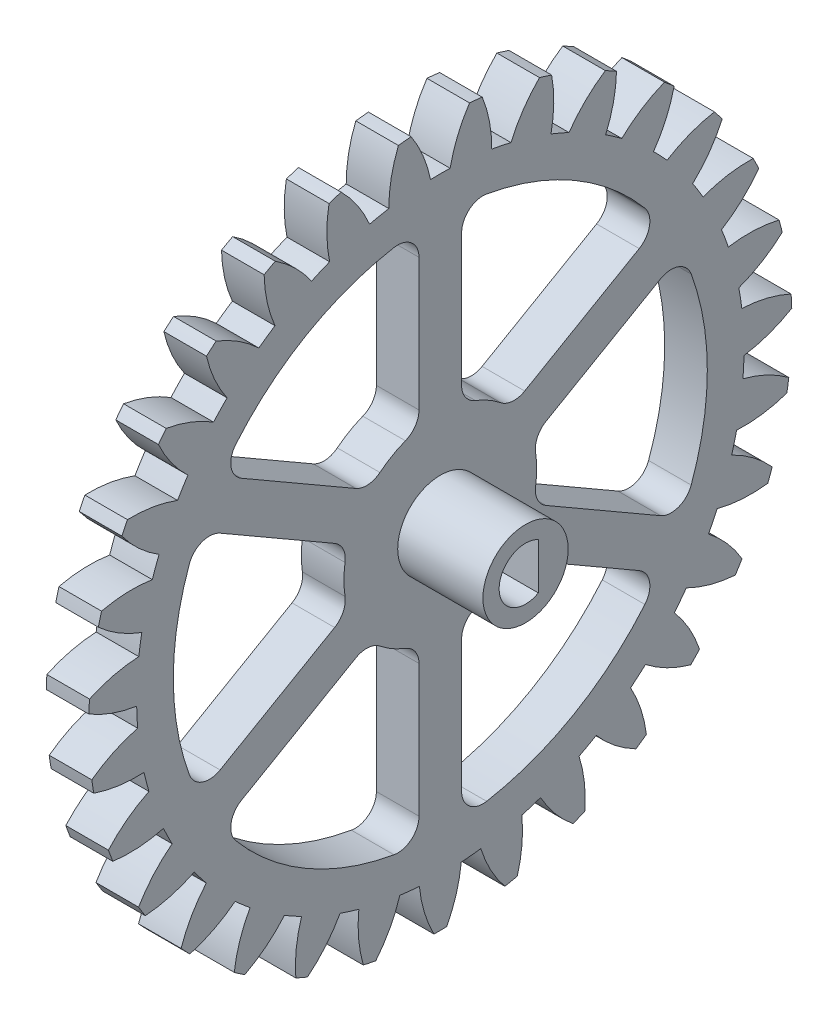
SolidWorks part; units mm, degrees
ref_plane "Plane1" through (0, 0, 0) normal (0, 0, 1) x (1, 0, 0)
ref_plane "Plane2" through (0, 0, 0) normal (0, 1, 0) x (1, 0, 0)
ref_plane "Plane3" through (0, 0, 0) normal (1, 0, 0) x (0, 0, -1)
sketch "HoldingSke" plane through (0, 0, 0) normal (0, 1, 0) x (1, 0, 0)
  line L0 (0, 0) -> (174.1764, -104.6557)
  line L1 (-15, 0) -> (100, 0) construction
  line L2 (0, 0) -> (-2.1039, 2.3779)
  line L3 (0, 0) -> (-11.863, 4.5341)
  line L4 (0, 0) -> (7.4025, 4.4479)
  line L5 (0, 0) -> (-47.5972, -17.7524)
  line L6 (0, 0) -> (-5.2639, -3.5516)
  line L7 (-2.1039, 2.3779) -> (8.8308, 51.9871)
  line L8 (-76.2, 54.61) -> (-72.771, 54.61)
  line L9 (-71.009, 38.7566) -> (-53.1078, 45.2721)
  line L10 (-76.2, 71.12) -> (104.1128, 71.12)
  line L11 (0, 0) -> (-6.35, 0)
  line L12 (-76.2, 101.6) -> (-76.0857, 101.6)
  line L13 (24.9733, 27.94) -> (52.9518, 28.4284)
  line L14 (24.9733, 27.94) -> (24.9746, 27.94)
  line L15 (24.9733, 27.94) -> (100.4006, 29.5858)
  circle A0 centre (0, 0) radius 1.5875
  circle A1 centre (0, 0) radius 38.1
  circle A2 centre (0, 0) radius 38.1
  circle A3 centre (0, 0) radius 1.5875
  dimension "MHD" = 76.2
  dimension "Hub_dia" = 76.2
  dimension "Bore" = 3.175
  dimension "MBD" = 3.175
  dimension "Num_teeth" = 31
  dimension "Pitch" = 203.2
  dimension "Overall_len" = 50.8
  dimension "Show_teeth" = 31
  dimension "Thickness" = 6.35
  dimension "OAL" = 50.8001
  dimension "T_dim" = 3.429
  dimension "Ap" = 20
  dimension "H" = 19.05
  dimension "Pitch_radius" = 180.3128
  dimension "Width" = 6.35
  dimension "Backlash" = 0.1143
  dimension "Addendum_fac" = 1
  dimension "Dedendum_fac" = 1.25
  dimension "Clearance_fac" = 0.25
  dimension "Dedendum_add" = 0.0013
sketch "BasProSke" plane through (0, 0, 0) normal (0, 1, 0) x (1, 0, 0)
  line L0 (-10, 0) -> (60, 0) construction
  line L1 (0, 0) -> (0, 52.3875)
  line L2 (0, 0) -> (6.35, 0)
  line L3 (6.35, 0) -> (6.35, 52.3875)
  line L4 (6.35, 52.3875) -> (0, 52.3875)
  dimension "Thickness" = 6.35
  dimension "Diameter" = 104.775
revolve "Base-Revolve" add sketch "BasProSke" angle 360 about L0
sketch "TooCutSke" plane through (0, 0, 0) normal (1, 0, 0) x (0, 0, -1)
  line L1 (0, 0) -> (0, 107) construction
  line L2 (0, 0) -> (-2.6926, 49.1388) construction
  line L3 (0, 0) -> (-9.9467, 97.8137) construction
  line L4 (-2.6926, 49.1388) -> (-4.9733, 48.9069) construction
  arc A0 (1.4638, 45.2188) -> (-1.4638, 45.2188) centre (0, 0) ccw
  arc A1 (4.3725, 52.2302) -> (-4.3725, 52.2302) centre (0, 0) ccw
  circle A2 centre (0, 0) radius 49.2125 construction
  circle A3 centre (0, 0) radius 46.2446 construction
  arc A4 (-1.4638, 45.2188) -> (-4.3725, 52.2302) centre (-20.7595, 41.3232) ccw
  arc A5 (4.3725, 52.2302) -> (1.4638, 45.2188) centre (20.7595, 41.3232) ccw
  dimension "Root_dia" = 90.485
  dimension "Overcut_dia" = 104.8258
  dimension "Pitch_dia" = 98.425
  dimension "Base_dia" = 92.4892
  dimension "Flank_rad" = 19.685
  dimension "Half_ang" = 5.806
  dimension "Half_CT" = 2.2925
extrude "ToothCut" cut sketch "TooCutSke" along normal through all
fillet "Breaks" [suppressed] radius 0.0635
fillet "RootFillets" [suppressed] radius 0.795
pattern_circular "TeethCuts" count 31 every 11.613 about axis through (-10, 0, 0) along (1, 0, 0) of "ToothCut", "RootFillets", "Breaks"
sketch "HubNeaOneSke" plane through (0, 0, 0) normal (-1, 0, 0) x (0, 0, 1)
  circle A0 centre (0, 0) radius 38.1
  dimension "Diameter" = 76.2
extrude "HubNearOne" [suppressed] add sketch "HubNeaOneSke" along normal blind 44.4501
sketch "HubNeaBotSke" plane through (0, 0, 0) normal (-1, 0, 0) x (0, 0, 1)
  circle A0 centre (0, 0) radius 38.1
  dimension "Diameter" = 76.2
extrude "HubNearBoth" [suppressed] add sketch "HubNeaBotSke" along normal blind 22.225
ref_plane "FarPln" through (6.35, 0, 0) normal (1, 0, 0) x (0, 0, -1)
sketch "HubFarSke" plane through (6.35, 0, 0) normal (1, 0, 0) x (0, 0, -1)
  circle A0 centre (0, 0) radius 38.1
  dimension "Diameter" = 76.2
extrude "HubFar" [suppressed] add sketch "HubFarSke" along normal blind 22.225
sketch "BorSke" plane through (0, 0, 0) normal (1, 0, 0) x (0, 0, -1)
  circle A0 centre (0, 0) radius 1.5875
  dimension "Diameter" = 3.175
extrude "Bore" cut sketch "BorSke" along normal mid plane 101.6001
sketch "KeySke" plane through (0, 0, 0) normal (1, 0, 0) x (0, 0, -1)
  line L0 (-0.127, 0) -> (-0.127, 1.8415)
  line L1 (-0.127, 1.8415) -> (0.127, 1.8415)
  line L2 (0.127, 1.8415) -> (0.127, 0)
  line L3 (0, 0) -> (0, 34) construction
  line L4 (-0.127, 0) -> (0.127, 0)
  dimension "Offset" = 1.8415
  dimension "Width" = 0.254
extrude "Keyway" [suppressed] cut sketch "KeySke" along normal mid plane 101.6001
pattern_circular "Keyway2" [suppressed] count 2 every 90 about axis through (-10, 0, 0) along (1, 0, 0)
sketch "Sketch1" plane through (6.35, 0, 0) normal (1, 0, 0) x (0, 0, -1)
  circle A0 centre (0, 0) radius 6.35
  dimension "D1" = 12.7
extrude "Boss-Extrude1" add sketch "Sketch1" along normal blind 12.7
sketch "Sketch2" plane through (19.05, 0, 0) normal (1, 0, 0) x (0, 0, -1)
  line L0 (1.905, 3.4454) -> (1.905, -3.4454)
  line L1 (3.937, 0) -> (-3.937, 0)
  circle A0 centre (0, 0) radius 3.937
  dimension "D1" = 7.874
  dimension "D2" = 5.842
extrude "Cut-Extrude1" cut sketch "Sketch2" against normal through all contours L0 A0 L1 | L1 A0 L0
sketch "Sketch3" plane through (6.35, 0, 0) normal (1, 0, 0) x (0, 0, -1)
  line L0 (0, 39.781) -> (0, -39.781) construction
  line L1 (-34.4514, 19.8905) -> (34.4514, -19.8905) construction
  line L2 (-34.4514, -19.8905) -> (34.4514, 19.8905) construction
  line L3 (-36.0389, 17.1409) -> (32.8639, -22.6401)
  line L4 (-32.8639, 22.6401) -> (36.0389, -17.1409)
  line L5 (-3.175, 39.781) -> (-3.175, -39.781)
  line L6 (3.175, 39.781) -> (3.175, -39.781)
  line L7 (-32.8639, -22.6401) -> (36.0389, 17.1409)
  line L8 (-36.0389, -17.1409) -> (32.8639, 22.6401)
  circle A0 centre (0, 0) radius 39.781
  circle A1 centre (0, 0) radius 14.3671
  dimension "D9" = 79.562
  dimension "D10" = 28.7342
  dimension "D1" = 60
  dimension "D2" = 60
  dimension "D3" = 3.175
  dimension "D4" = 3.175
  dimension "D5" = 3.175
  dimension "D6" = 3.175
  dimension "D7" = 3.175
  dimension "D8" = 3.175
extrude "Cut-Extrude2" cut sketch "Sketch3" against normal through all contours A1 L5 A0 L4 | A1 L3 A0 L8 | A1 L7 A0 L5 | A1 L6 A0 L3 | A1 L4 A0 L7 | A1 L8 A0 L6
fillet "Fillet1" radius 3.175 24 edges at (3.175, 4.2563, 13.7222) (3.175, -9.7556, -10.5472) (3.175, -14.0119, 3.175) (3.175, 14.0119, 3.175) (3.175, -4.2563, 13.7222) (3.175, 9.7556, -10.5472) (3.175, -22.5767, 32.754) (3.175, 17.0774, -35.929) (3.175, -9.7556, 10.5472) (3.175, 4.2563, -13.7222) (3.175, -14.0119, -3.175) (3.175, 14.0119, -3.175) (3.175, 17.0774, 35.929) (3.175, -22.5767, -32.754) (3.175, -39.6541, -3.175) (3.175, 39.6541, -3.175) (3.175, -4.2563, -13.7222) (3.175, 9.7556, 10.5472) (3.175, -17.0774, 35.929) (3.175, 22.5767, -32.754) (3.175, -17.0774, -35.929) (3.175, 22.5767, 32.754) (3.175, -39.6541, 3.175) (3.175, 39.6541, 3.175)
equation "' \"Pitch@HoldingSke\" = 4"
equation "' \"Num_teeth@HoldingSke\" = 12"
equation "' \"Ap@HoldingSke\" =  20"
equation "' \"Ap@HoldingSke\" = 20"
equation "' \"Width@HoldingSke\" = 0.5"
equation "' \"Hub_dia@HoldingSke\"= 1"
equation "' \"Hub_dia@HoldingSke\" = 1"
equation "' \"Overall_len@HoldingSke\" = 1.0"
equation "' \"Bore@HoldingSke\" = 0.75"
equation "' \"T_dim@HoldingSke\" = 0.85"
equation "' \"Width@KeySke\" = 0.25"
equation "' \"Show_teeth@HoldingSke\" = 13"
equation "' \"Backlash@HoldingSke\" = 0.009"
equation "' \"Addendum_fac@HoldingSke\" = 1.0"
equation "' \"Dedendum_fac@HoldingSke\" = 1.25"
equation "' \"Dedendum_add@HoldingSke\" = 0.00005"
equation "' \"Clearance_fac@HoldingSke\" = 0.25"
equation "' \"Pitch@HoldingSke\" = 0.5"
equation "' \"Num_teeth@HoldingSke\" = 23"
equation "' \"Show_teeth@HoldingSke\" = 23"
equation "' \"Backlash@HoldingSke\" = 0.0375"
equation "\"Overcut_dia@TooCutSke\" = (\"Num_teeth@HoldingSke\" + 2 * \"Addendum_fac@HoldingSke\") / \"Pitch@HoldingSke\" + 0.002"
equation "\"Pitch_dia@TooCutSke\" = \"Num_teeth@HoldingSke\" / \"Pitch@HoldingSke\""
equation "\"Base_dia@TooCutSke\" = \"Num_teeth@HoldingSke\" / \"Pitch@HoldingSke\" * cos((\"Ap@HoldingSke\"  * 3.14159265 / 180))"
equation "\"Root_dia@TooCutSke\" = (\"Num_teeth@HoldingSke\" + 2) / \"Pitch@HoldingSke\" - 2 * (\"Addendum_fac@HoldingSke\" + \"Dedendum_fac@HoldingSke\") / \"Pitch@HoldingSke\" - \"Dedendum_add@HoldingSke\" * 2"
equation "\"Half_ang@TooCutSke\" = 180 / \"Num_teeth@HoldingSke\""
equation "\"Half_CT@TooCutSke\" = \"Num_teeth@HoldingSke\" / \"Pitch@HoldingSke\" * sin((3.14159265 / 2 / \"Num_teeth@HoldingSke\")) / 2 - 7 * \"Backlash@HoldingSke\" / 4"
equation "\"Flank_rad@TooCutSke\" = \"Num_teeth@HoldingSke\" / \"Pitch@HoldingSke\" / 5"
equation "\"Radius@RootFillets\" = \"Clearance_fac@HoldingSke\" / \"Pitch@HoldingSke\" + \"Dedendum_add@HoldingSke\""
equation "\"Break_rad@Breaks\" = 0.02 / \"Pitch@HoldingSke\""
equation "\"Thickness@HoldingSke\" = \"Width@HoldingSke\""
equation "\"OAL@HoldingSke\" = \"Thickness@HoldingSke\""
equation "\"MHD@HoldingSke\" = (\"Num_teeth@HoldingSke\" + 2) / \"Pitch@HoldingSke\" - 2 * (\"Addendum_fac@HoldingSke\" + \"Dedendum_fac@HoldingSke\")  / \"Pitch@HoldingSke\" - \"Dedendum_add@HoldingSke\" * 2"
equation "\"MBD@HoldingSke\" = (\"Num_teeth@HoldingSke\" + 2) / \"Pitch@HoldingSke\" - 2 * (\"Addendum_fac@HoldingSke\" + \"Dedendum_fac@HoldingSke\")  / \"Pitch@HoldingSke\" - \"Dedendum_add@HoldingSke\" * 2 - 0.002"
equation "\"MHD@HoldingSke\" = ((sgn( \"MHD@HoldingSke\" - \"Hub_dia@HoldingSke\" )-1)*( \"MHD@HoldingSke\" - \"Hub_dia@HoldingSke\" ))/-2+ \"Hub_dia@HoldingSke\""
equation "\"MBD@HoldingSke\" = ((sgn( \"MBD@HoldingSke\" - \"Bore@HoldingSke\" )-1)*( \"MBD@HoldingSke\" - \"Bore@HoldingSke\" ))/-2+ \"Bore@HoldingSke\""
equation "\"OAL@HoldingSke\" = ((sgn( \"OAL@HoldingSke\" - \"Overall_len@HoldingSke\" )+1)*( \"OAL@HoldingSke\" - \"Overall_len@HoldingSke\" ))/2 + \"Overall_len@HoldingSke\" + 0.000002"
equation "\"Num_teeth@TeethCuts\" = int( \"Show_teeth@HoldingSke\" ) + 1"
equation "\"Num_teeth@TeethCuts\" = ((sgn( \"Num_teeth@TeethCuts\" - \"Num_teeth@HoldingSke\" )-1)*( \"Num_teeth@TeethCuts\" - \"Num_teeth@HoldingSke\" ))/-2+ \"Num_teeth@HoldingSke\""
equation "\"Num_teeth@TeethCuts\" = ((sgn( \"Num_teeth@TeethCuts\" - 2.0)+1)*( \"Num_teeth@TeethCuts\" - 2.0))/2 +2.0"
equation "\"Angle@TeethCuts\" = 360.0 / \"Num_teeth@HoldingSke\""
equation "\"Diameter@BasProSke\" = (\"Num_teeth@HoldingSke\" + 2 * \"Addendum_fac@HoldingSke\") / \"Pitch@HoldingSke\""
equation "\"Thickness@BasProSke\"  = \"Thickness@HoldingSke\""
equation "' \"Fillet_rad@BasProSke\" =  \"Thickness@HoldingSke\" * 0.05"
equation "' \"Fillet_rad@BasProSke\" = \"Thickness@HoldingSke\" * 0.05"
equation "\"MHD@HoldingSke\" = ((sgn( \"MHD@HoldingSke\" - \"Root_dia@TooCutSke\" )-1)*( \"MHD@HoldingSke\" - \"Root_dia@TooCutSke\" ))/-2+ \"Root_dia@TooCutSke\""
equation "\"Diameter@HubNeaOneSke\" = \"MHD@HoldingSke\""
equation "\"Length@HubNearOne\" = \"OAL@HoldingSke\" - \"Thickness@BasProSke\""
equation "\"Diameter@HubNeaBotSke\" = \"MHD@HoldingSke\""
equation "\"Length@HubNearBoth\" = ( \"OAL@HoldingSke\" - \"Thickness@BasProSke\" ) / 2.0"
equation "\"Thickness@FarPln\" = \"Thickness@BasProSke\""
equation "\"Diameter@HubFarSke\" = \"MHD@HoldingSke\""
equation "\"Length@HubFar\" = ( \"OAL@HoldingSke\" - \"Thickness@BasProSke\" ) / 2.0"
equation "\"Diameter@BorSke\" = \"MBD@HoldingSke\""
equation "\"D1@Bore\" = \"OAL@HoldingSke\" * 2.0"
equation "\"D1@Keyway\" = \"OAL@HoldingSke\" * 2.0"
equation "\"Offset@KeySke\" = \"T_dim@HoldingSke\" - \"MBD@HoldingSke\" / 2.0"
